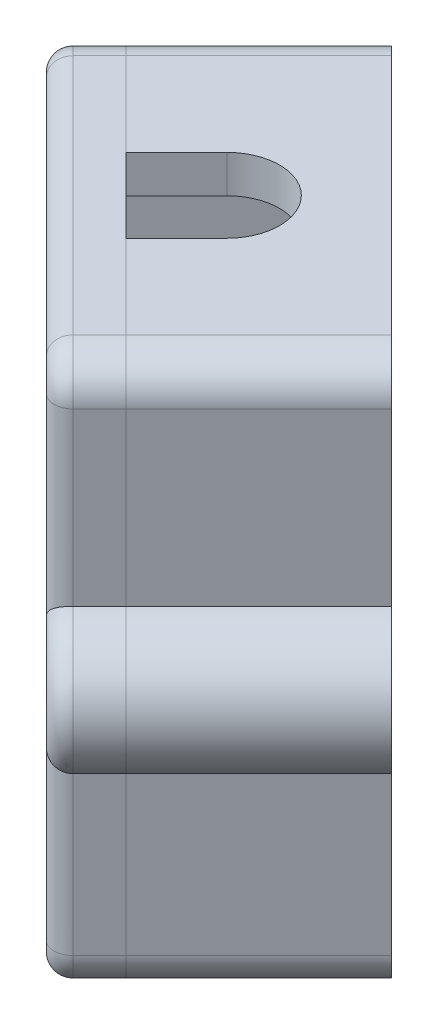
SolidWorks part; units mm, degrees
ref_plane "Front Plane" through (0, 0, 0) normal (0, 0, 1) x (1, 0, 0)
ref_plane "Top Plane" through (0, 0, 0) normal (0, 1, 0) x (1, 0, 0)
ref_plane "Right Plane" through (0, 0, 0) normal (1, 0, 0) x (0, 0, -1)
sketch "Sketch1" plane through (-69.3942, 0, 69.3942) normal (-0.7071, 0, 0.7071) x (0.7071, 0, 0.7071)
  line L0 (-46.9518, 17.5) -> (-24.9518, 17.5) construction
  line L1 (-47.0518, 20.9986) -> (-47.0518, 30.1)
  line L3 (-45.0518, 2.9) -> (-26.8518, 2.9)
  line L4 (-47.0518, 4.9) -> (-47.0518, 14.0014)
  line L11 (-45.0518, 32.1) -> (-26.8518, 32.1)
  line L12 (-24.8518, 4.9) -> (-24.8518, 14.0014)
  line L13 (-35.9518, 32.1) -> (-35.9518, 2.9) construction
  line L14 (-47.0518, 17.5) -> (-24.8518, 17.5) construction
  line L15 (-24.8518, 20.9986) -> (-24.8518, 30.1)
  line L16 (-57.2818, 4) -> (-14.6218, 4) construction
  arc A6 (-47.0518, 20.9986) -> (-47.0518, 14.0014) centre (-46.9518, 17.5) ccw
  arc A7 (-24.8518, 14.0014) -> (-24.8518, 20.9986) centre (-24.9518, 17.5) ccw
  arc A8 (-45.0518, 2.9) -> (-47.0518, 4.9) centre (-45.0518, 4.9) cw
  arc A9 (-26.8518, 2.9) -> (-24.8518, 4.9) centre (-26.8518, 4.9) ccw
  arc A10 (-26.8518, 32.1) -> (-24.8518, 30.1) centre (-26.8518, 30.1) cw
  arc A11 (-47.0518, 30.1) -> (-45.0518, 32.1) centre (-45.0518, 30.1) cw
  point P4 (-35.9518, 17.5)
  point P6 (-35.9518, 17.1556)
  dimension "D3" = 2
  dimension "D5" = 3.5
  dimension "D1" = 29.2
  dimension "D2" = 22.2
  dimension "D4" = 13.1556
  dimension "D6" = 10.23
  dimension "D7" = 10.33
  dimension "D8" = 10.0014
extrude "Boss-Extrude1" add sketch "Sketch1" along normal blind 10
sketch "Sketch2" plane through (-76.4653, 0, 76.4653) normal (-0.7071, 0, 0.7071) x (0.7071, 0, 0.7071)
  line L0 (-35.9518, 32.1) -> (-35.9518, 2.9) construction
  line L1 (-26.8518, 32.1) -> (-45.0518, 32.1) construction
  line L2 (-45.0518, 2.9) -> (-26.8518, 2.9) construction
  line L3 (-24.9518, 17.5) -> (-46.9518, 17.5) construction
  circle A0 centre (-46.9518, 17.5) radius 1.125
  circle A1 centre (-24.9518, 17.5) radius 1.125
extrude "Cut-Extrude1" cut sketch "Sketch2" against normal up to next
sketch "Sketch3" plane through (-76.4653, 0, 76.4653) normal (-0.7071, 0, 0.7071) x (0.7071, 0, 0.7071)
  line L0 (-35.9518, 32.1) -> (-35.9518, 2.9) construction
  line L1 (-26.8518, 32.1) -> (-45.0518, 32.1) construction
  line L2 (-45.0518, 2.9) -> (-26.8518, 2.9) construction
  line L3 (-21.4518, 17.5) -> (-50.4518, 17.5) construction
  line L5 (-45.0518, 4.9) -> (-26.8518, 4.9)
  line L6 (-45.0518, 4.9) -> (-45.0518, 30.1)
  line L7 (-45.0518, 30.1) -> (-26.8518, 30.1)
  line L8 (-26.8518, 4.9) -> (-26.8518, 30.1)
  line L9 (-35.9518, 30.1) -> (-35.9518, 4.9) construction
  line L10 (-45.0518, 17.5) -> (-26.8518, 17.5) construction
  arc A0 (-24.8518, 14.0014) -> (-24.8518, 20.9986) centre (-24.9518, 17.5) ccw construction
  arc A1 (-47.0518, 20.9986) -> (-47.0518, 14.0014) centre (-46.9518, 17.5) ccw construction
  point P14 (-35.9518, 17.5)
  dimension "D1" = 25.2
  dimension "D2" = 18.2
extrude "Cut-Extrude2" cut sketch "Sketch3" against normal blind 8
sketch "Sketch4" plane through (0, 32.1, 0) normal (0, 1, 0) x (1, 0, 0)
  line L1 (-95.4524, -57.4782) -> (-108.3218, -44.6089) construction
  line L2 (-88.3813, -50.4071) -> (-101.2507, -37.5378) construction
  line L3 (-95.2403, -48.3565) -> (-86.9671, -56.6297) construction
  line L5 (-91.634, -61.2966) -> (-84.563, -54.2255) construction
  line L6 (-103.867, -49.0636) -> (-101.18, -46.3766)
  line L7 (-103.867, -49.0636) -> (-99.9072, -53.0234)
  line L9 (-99.9072, -53.0234) -> (-97.2202, -50.3364)
  line L12 (-97.2202, -46.3766) -> (-94.816, -43.9725) construction
  arc A0 (-97.2202, -50.3364) -> (-101.18, -46.3766) centre (-99.2001, -48.3565) ccw
  dimension "D1" = 6.6
  dimension "D2" = 5.6
extrude "Cut-Extrude3" cut sketch "Sketch4" against normal up to next
sketch "Sketch5" plane through (-76.4653, 0, 76.4653) normal (-0.7071, 0, 0.7071) x (0.7071, 0, 0.7071)
  line L0 (-47.0518, 20.9986) -> (-47.0518, 30.1)
  line L1 (-47.0518, 20.9986) -> (-47.0518, 30.1)
  line L2 (-45.0518, 32.1) -> (-26.8518, 32.1)
  line L3 (-45.0518, 32.1) -> (-26.8518, 32.1)
  line L4 (-24.8518, 30.1) -> (-24.8518, 20.9986)
  line L5 (-24.8518, 30.1) -> (-24.8518, 20.9986)
  line L6 (-24.8518, 14.0014) -> (-24.8518, 4.9)
  line L7 (-24.8518, 14.0014) -> (-24.8518, 4.9)
  line L8 (-26.8518, 2.9) -> (-45.0518, 2.9)
  line L9 (-26.8518, 2.9) -> (-45.0518, 2.9)
  line L10 (-47.0518, 4.9) -> (-47.0518, 14.0014)
  line L11 (-47.0518, 4.9) -> (-47.0518, 14.0014)
  line L12 (-35.9518, 32.1) -> (-35.9518, 2.9) construction
  line L13 (-45.0518, 4.9) -> (-26.8518, 4.9) construction
  line L14 (-40.9518, 9.9) -> (-30.9518, 9.9)
  line L15 (-40.9518, 9.9) -> (-40.9518, 4.9)
  line L16 (-40.9518, 4.9) -> (-30.9518, 4.9)
  line L17 (-30.9518, 9.9) -> (-30.9518, 4.9)
  line L18 (-35.9518, 4.9) -> (-35.9518, 9.9) construction
  line L19 (-40.9518, 7.4) -> (-30.9518, 7.4) construction
  line L20 (-24.8518, 4.9) -> (-24.8518, 14.0014) construction
  line L21 (-45.0518, 2.9) -> (-26.8518, 2.9) construction
  arc A0 (-45.0518, 32.1) -> (-47.0518, 30.1) centre (-45.0518, 30.1) ccw
  arc A1 (-45.0518, 32.1) -> (-47.0518, 30.1) centre (-45.0518, 30.1) ccw
  arc A2 (-24.8518, 30.1) -> (-26.8518, 32.1) centre (-26.8518, 30.1) ccw
  arc A3 (-24.8518, 30.1) -> (-26.8518, 32.1) centre (-26.8518, 30.1) ccw
  arc A4 (-24.8518, 14.0014) -> (-24.8518, 20.9986) centre (-24.9518, 17.5) ccw
  arc A5 (-24.8518, 14.0014) -> (-24.8518, 20.9986) centre (-24.9518, 17.5) ccw
  arc A6 (-26.8518, 2.9) -> (-24.8518, 4.9) centre (-26.8518, 4.9) ccw
  arc A7 (-26.8518, 2.9) -> (-24.8518, 4.9) centre (-26.8518, 4.9) ccw
  arc A8 (-47.0518, 4.9) -> (-45.0518, 2.9) centre (-45.0518, 4.9) ccw
  arc A9 (-47.0518, 4.9) -> (-45.0518, 2.9) centre (-45.0518, 4.9) ccw
  arc A10 (-47.0518, 20.9986) -> (-47.0518, 14.0014) centre (-46.9518, 17.5) ccw
  arc A11 (-47.0518, 20.9986) -> (-47.0518, 14.0014) centre (-46.9518, 17.5) ccw
  circle A12 centre (-46.9518, 17.5) radius 1.25
  circle A13 centre (-24.9518, 17.5) radius 1.25
  point P22 (-35.9518, 7.4)
  dimension "D1" = 5
  dimension "D3" = 2.5
  dimension "D2" = 10
extrude "Boss-Extrude2" add sketch "Sketch5" along normal blind 3 separate body
fillet "Fillet1" radius 1 12 edges at (-111.4431, 3.4858, 45.7302) (-104.0084, 2.9, 53.1648) (-96.5737, 3.4858, 60.5995) (-96.1595, 9.4507, 61.0137) (-93.7554, 17.5, 63.4179) (-96.1595, 25.5493, 61.0137) (-96.5737, 31.5142, 60.5995) (-104.0084, 32.1, 53.1648) (-111.4431, 31.5142, 45.7302) (-111.8573, 25.5493, 45.316) (-114.2615, 17.5, 42.9118) (-111.8573, 9.4507, 45.316)
